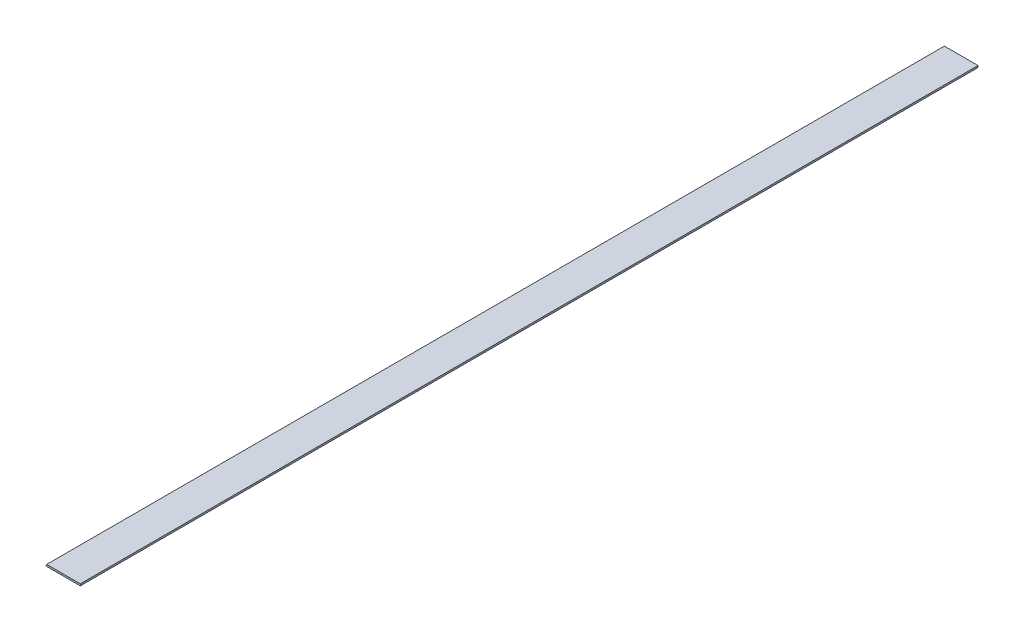
SolidWorks part; units mm, degrees
ref_plane "Front Plane" through (0, 0, 0) normal (0, 0, 1) x (1, 0, 0)
ref_plane "Top Plane" through (0, 0, 0) normal (0, 1, 0) x (1, 0, 0)
ref_plane "Right Plane" through (0, 0, 0) normal (1, 0, 0) x (0, 0, -1)
sketch "Sketch1" plane through (0, 0, 0) normal (0, 0, 1) x (1, 0, 0)
  line L0 (0, 0) -> (0.3817, 1) construction
  line L1 (0.3817, 1) -> (20.1917, 1)
  line L2 (20.1917, 1) -> (20.1917, 0)
  line L3 (20.1917, 0) -> (0, 0)
  line L4 (1, 0) -> (1.3817, 1)
  dimension "D1" = 19.81
  dimension "D2" = 20.1917
  dimension "D3" = 1
  dimension "D4" = 1
  dimension "D5" = 1
extrude "Boss-Extrude1" add sketch "Sketch1" along normal blind 502 contours L4 L3 L2 L1
